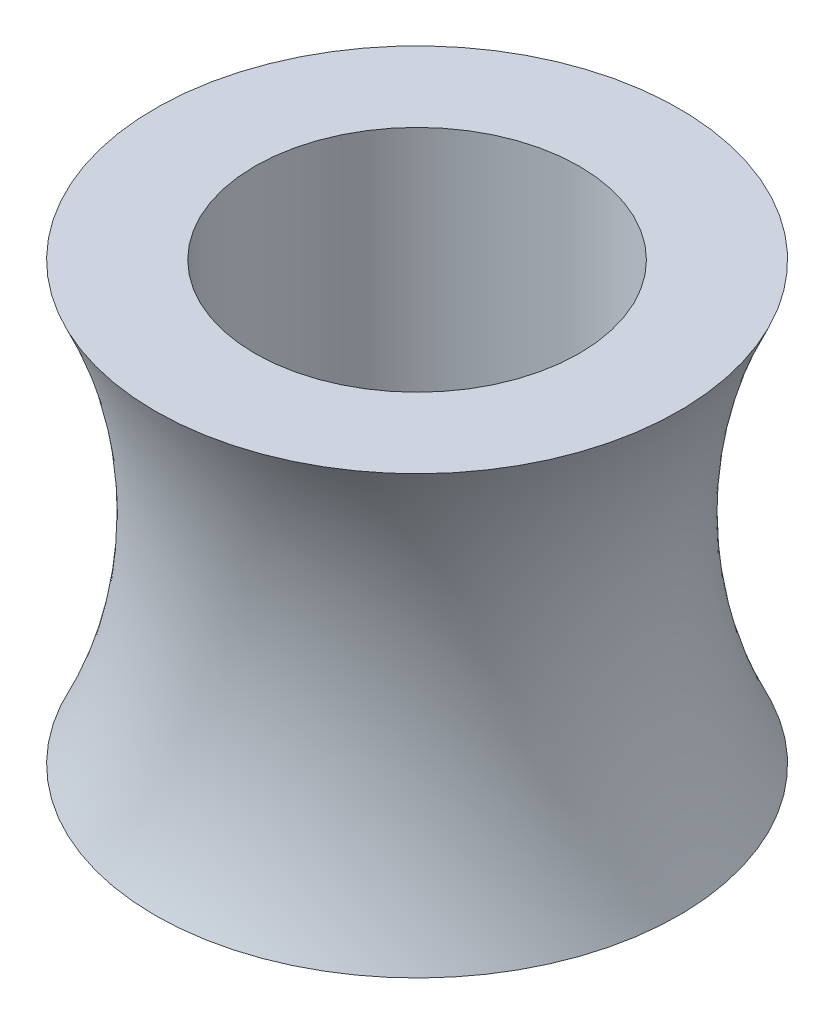
SolidWorks part; units mm, degrees
ref_plane "Front Plane" through (0, 0, 0) normal (0, 0, 1) x (1, 0, 0)
ref_plane "Top Plane" through (0, 0, 0) normal (0, 1, 0) x (1, 0, 0)
ref_plane "Right Plane" through (0, 0, 0) normal (1, 0, 0) x (0, 0, -1)
sketch "Sketch1" plane through (0, 0, 0) normal (0, 1, 0) x (1, 0, 0)
  circle A0 centre (0, 0) radius 6.5
  circle A1 centre (0, 0) radius 8.5
  dimension "D1" = 13
  dimension "D2" = 17
extrude "Boss-Extrude1" add sketch "Sketch1" along normal blind 17.5
sketch "Sketch2" plane through (0, 0, 0) normal (0, 0, 1) x (1, 0, 0)
  line L0 (6.5, 17.5) -> (6.5, 0)
  line L1 (6.5, 0) -> (10.5, 0)
  line L2 (6.5, 17.5) -> (10.5, 17.5)
  line L6 (0, -11.55) -> (0, 11.55) construction
  line L7 (-8.5, 0) -> (8.5, 0) construction
  arc A0 (10.5, 0) -> (10.5, 17.5) centre (28.6406, 8.75) cw
  dimension "D1" = 6.5
  dimension "D2" = 4
  dimension "D3" = 17.5
ref_axis "Axis1" through (0, 65.415, 0) along (0, -1, 0)
revolve "Revolve1" add sketch "Sketch2" angle 360 about axis through (0, 65.415, 0) along (0, -1, 0)
